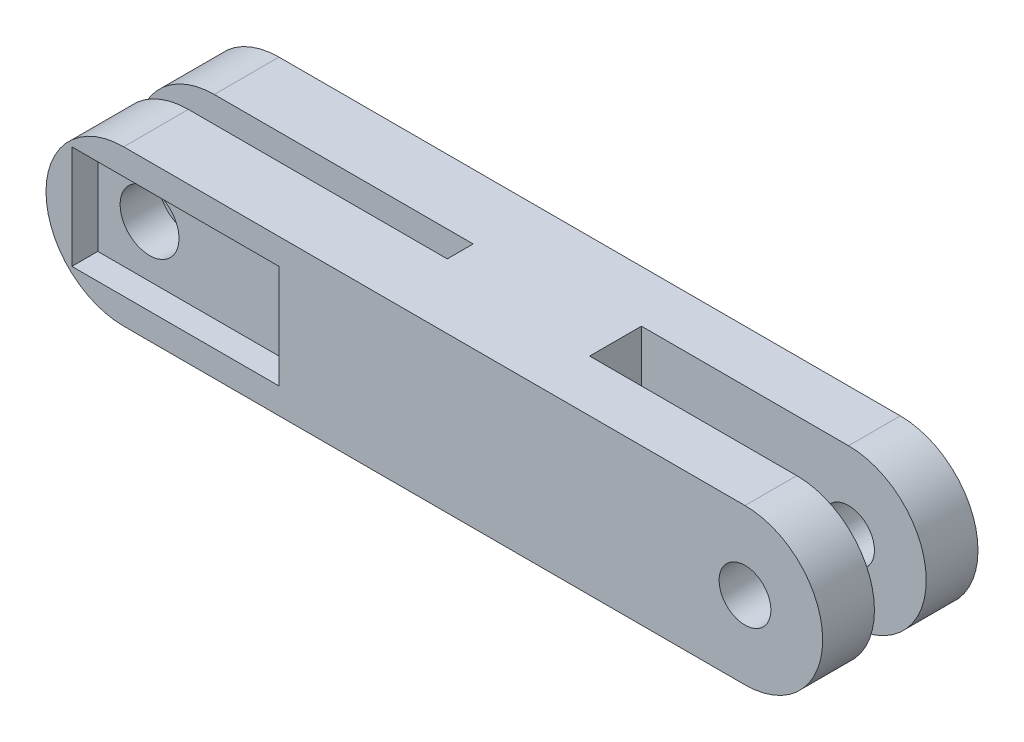
SolidWorks part; units mm, degrees
material "PVC Rigid"
ref_plane "Front Plane" through (0, 0, 0) normal (0, 0, 1) x (1, 0, 0)
ref_plane "Top Plane" through (0, 0, 0) normal (0, 1, 0) x (1, 0, 0)
ref_plane "Right Plane" through (0, 0, 0) normal (1, 0, 0) x (0, 0, -1)
sketch "Sketch1" plane through (0, 0, 0) normal (0, 0, 1) x (1, 0, 0)
  line L1 (-104.4163, 20.7238) -> (47.9837, 20.7238)
  line L3 (-104.4163, -17.3762) -> (47.9837, -17.3762)
  arc A0 (-104.4163, 20.7238) -> (-104.4163, -17.3762) centre (-104.4163, 1.6738) ccw
  arc A1 (47.9837, 20.7238) -> (47.9837, -17.3762) centre (47.9837, 1.6738) cw
  circle A3 centre (47.9837, 1.6738) radius 6.35
  circle A4 centre (-104.4163, 1.6738) radius 7.22
  point P6 (-123.4663, 1.6738)
  point P7 (67.0337, 1.6738)
  dimension "D3" = 19.05
  dimension "D5" = 19.05
  dimension "D1" = 190.5
  dimension "D2" = 38.1
extrude "Boss-Extrude1" add sketch "Sketch1" along normal blind 38.1
sketch "Sketch2" plane through (0, 0, 38.1) normal (0, 0, 1) x (1, 0, 0)
  line L1 (-117.1163, 14.3738) -> (-66.3163, 14.3738)
  line L2 (-117.1163, 14.3738) -> (-117.1163, -11.0262)
  line L3 (-117.1163, -11.0262) -> (-66.3163, -11.0262)
  line L4 (-66.3163, 14.3738) -> (-66.3163, -11.0262)
  circle A3 centre (-104.4163, 1.6738) radius 7.22 construction
  dimension "D3" = 12.7
  dimension "D4" = 12.7
  dimension "D1" = 50.8
  dimension "D2" = 25.4
extrude "Cut-Extrude1" cut sketch "Sketch2" against normal blind 6.35
sketch "Sketch4" plane through (0, 20.7238, 0) normal (0, 1, 0) x (1, 0, 0)
  line L0 (47.9837, 0) -> (-104.4163, 0) construction
  line L1 (-40.9163, -22.225) -> (-117.1163, -22.225)
  line L2 (-40.9163, -22.225) -> (-40.9163, -15.875)
  line L3 (-40.9163, -15.875) -> (-117.1163, -15.875)
  line L4 (-117.1163, -22.225) -> (-117.1163, -15.875)
  line L6 (-104.4163, -38.1) -> (-104.4163, 0) construction
  point P6 (-117.1163, -19.05)
  dimension "D1" = 15.875
  dimension "D2" = 76.2
  dimension "D3" = 6.35
  dimension "D4" = 63.5
sketch "Sketch5" plane through (0, 0, 0) normal (0, 1, 0) x (1, 0, 0)
  line L0 (47.9837, -38.1) -> (47.9837, 0) construction
  line L1 (-2.8163, -12.7) -> (73.3837, -12.7)
  line L2 (-2.8163, -12.7) -> (-2.8163, -25.4)
  line L3 (-2.8163, -25.4) -> (73.3837, -25.4)
  line L4 (73.3837, -12.7) -> (73.3837, -25.4)
  line L5 (47.9837, 0) -> (-104.4163, 0) construction
  dimension "D1" = 50.8
  dimension "D2" = 76.2
  dimension "D3" = 12.7
  dimension "D4" = 12.7
extrude "Cut-Extrude2" cut sketch "Sketch5" against normal through all both and the other way through all
extrude "Cut-Extrude3" cut sketch "Sketch4" against normal blind 31.75
sketch "Sketch7" plane through (0, 20.7238, 0) normal (0, 1, 0) x (1, 0, 0)
  line L0 (47.9837, -38.1) -> (-104.4163, -38.1) construction
  line L1 (-134.7315, -15.875) -> (-102.0318, -15.875)
  line L2 (-134.7315, -15.875) -> (-134.7315, -22.225)
  line L3 (-134.7315, -22.225) -> (-102.0318, -22.225)
  line L4 (-102.0318, -15.875) -> (-102.0318, -22.225)
  dimension "D1" = 6.35
  dimension "D2" = 15.875
extrude "Cut-Extrude4" cut sketch "Sketch7" against normal blind 19.05
